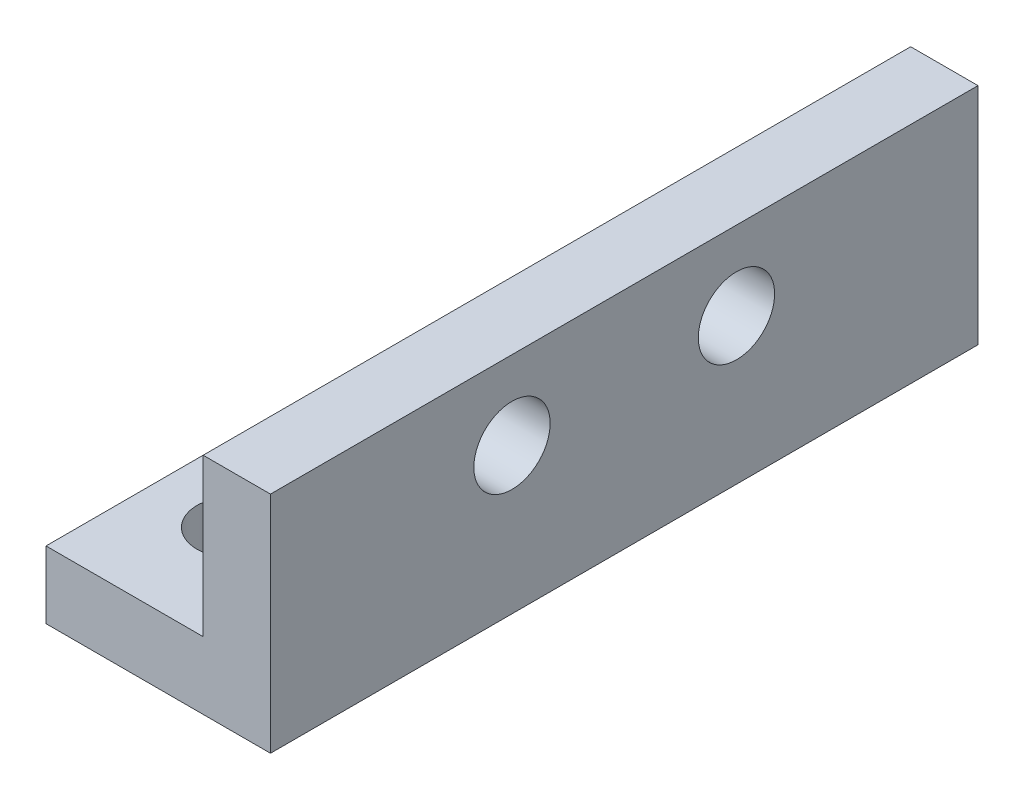
SolidWorks part; units mm, degrees
ref_plane "正面" through (0, 0, 0) normal (0, 0, 1) x (1, 0, 0)
ref_plane "平面" through (0, 0, 0) normal (0, 1, 0) x (1, 0, 0)
ref_plane "右側面" through (0, 0, 0) normal (1, 0, 0) x (0, 0, -1)
sketch "ｽｹｯﾁ1" plane through (0, 0, 0) normal (0, 0, 1) x (1, 0, 0)
  line L0 (-5, -2) -> (2, -2)
  line L1 (2, -2) -> (2, 5)
  line L2 (2, 5) -> (5, 5)
  line L3 (5, 5) -> (5, -5)
  line L4 (5, -5) -> (-5, -5)
  line L5 (-5, -5) -> (-5, -2)
  point P6 (0, -5)
  point P8 (5, 0)
  dimension "D1" = 3
  dimension "D2" = 10
  dimension "D3" = 10
extrude "ﾎﾞｽ - 押し出し1" add sketch "ｽｹｯﾁ1" along normal blind 31.52
hole_wizard "M3 すきま穴1" positions "ｽｹｯﾁ2" profile "ｽｹｯﾁ3" hole size "M3" standard "JIS" end condition through all
sketch "ｽｹｯﾁ2" plane through (0, -2, 0) normal (0, 1, 0) x (1, 0, 0)
  line L0 (-1.5, -4.935) -> (-1.5, -26.585) construction
  line L2 (-5, -31.52) -> (-5, 0) construction
  line L3 (2, 0) -> (-5, 0) construction
  point P0 (-1.5, -4.935)
  point P2 (-1.5, -26.585)
  point P12 (-5, -15.76)
  point P13 (-1.5, -15.76)
  point P16 (-1.5, 0)
  dimension "D1" = 21.65
sketch "ｽｹｯﾁ3" plane through (-1.5, -2, 4.935) normal (1, 0, 0) x (0, 0, 1)
  line L0 (0, 0) -> (0, 3)
  line L1 (0, 3) -> (1.7, 3)
  line L2 (1.7, 3) -> (1.7, 0)
  line L5 (1.7, 0) -> (0, 0)
  line L11 (0, -6.35) -> (0, 107.95) construction
  dimension "通し穴の直径" = 3.4
  dimension "通し穴の深さ" = 3
hole_wizard "M3 すきま穴2" positions "ｽｹｯﾁ4" profile "ｽｹｯﾁ5" hole size "M3" standard "JIS" end condition through all
sketch "ｽｹｯﾁ4" plane through (2, 0, 0) normal (-1, 0, 0) x (0, 0, 1)
  line L0 (10.76, 1.5) -> (20.76, 1.5) construction
  line L3 (31.52, 5) -> (0, 5) construction
  line L4 (0, 5) -> (0, -2) construction
  point P1 (10.76, 1.5)
  point P2 (20.76, 1.5)
  point P17 (15.76, 5)
  point P18 (15.76, 1.5)
  point P21 (0, 1.5)
  dimension "D1" = 10
sketch "ｽｹｯﾁ5" plane through (2, 1.5, 10.76) normal (0, 1, 0) x (0, 0, 1)
  line L0 (0, 0) -> (0, 3)
  line L1 (0, 3) -> (1.7, 3)
  line L2 (1.7, 3) -> (1.7, 0)
  line L5 (1.7, 0) -> (0, 0)
  line L11 (0, -6.35) -> (0, 107.95) construction
  dimension "通し穴の直径" = 3.4
  dimension "通し穴の深さ" = 3
